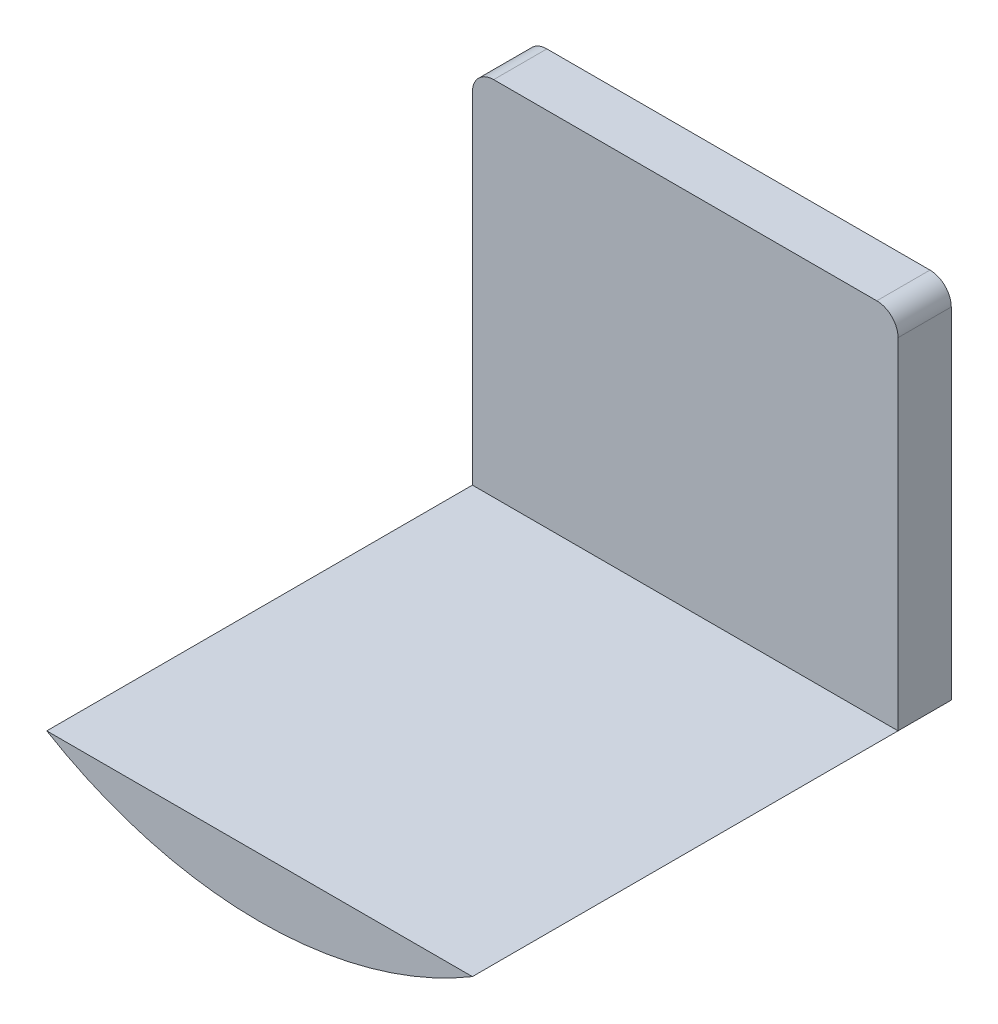
SolidWorks part; units mm, degrees
ref_plane "Front Plane" through (0, 0, 0) normal (0, 0, 1) x (1, 0, 0)
ref_plane "Top Plane" through (0, 0, 0) normal (0, 1, 0) x (1, 0, 0)
ref_plane "Right Plane" through (0, 0, 0) normal (1, 0, 0) x (0, 0, -1)
sketch "Sketch1" plane through (0, 0, 0) normal (0, 0, 1) x (1, 0, 0)
  line L0 (-25.4, -42.5213) -> (25.4, -42.5213)
  arc A0 (-25.4, -42.5213) -> (25.4, -42.5213) centre (0, 0) ccw
  dimension "D1" = 99.06
  dimension "D2" = 50.8
extrude "Boss-Extrude1" add sketch "Sketch1" along normal blind 57.15
sketch "Sketch2" plane through (0, -42.5213, 0) normal (0, 1, 0) x (1, 0, 0)
  line L0 (25.4, -57.15) -> (25.4, 0) construction
  line L1 (-25.4, 0) -> (25.4, 0)
  line L2 (-25.4, 0) -> (-25.4, -6.35)
  line L3 (-25.4, -6.35) -> (25.4, -6.35)
  line L4 (25.4, 0) -> (25.4, -6.35)
  dimension "D1" = 6.35
extrude "Boss-Extrude2" add sketch "Sketch2" along normal blind 43.18
fillet "Fillet1" radius 2.54 2 edges at (25.4, 0.6587, 3.175) (-25.4, 0.6587, 3.175)
